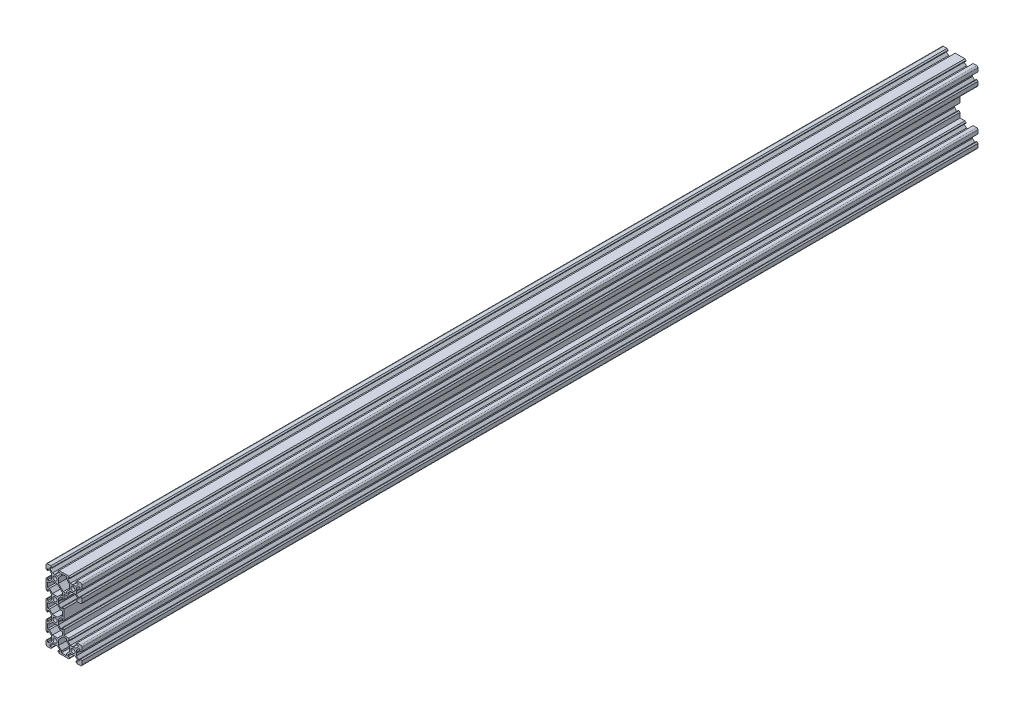
SolidWorks part; units mm, degrees
material "6061-T6 (SS)"
ref_plane "Front Plane" through (0, 0, 0) normal (0, 0, 1) x (1, 0, 0)
ref_plane "Top Plane" through (0, 0, 0) normal (0, 1, 0) x (1, 0, 0)
ref_plane "Right Plane" through (0, 0, 0) normal (1, 0, 0) x (0, 0, -1)
sketch "Sketch1" plane through (0, 0, 0) normal (0, 0, 1) x (1, 0, 0)
  line L0 (-20, -38.5) -> (-20, 38.5)
  line L1 (-18.5, 40) -> (18.5, 40)
  line L2 (20, 38.5) -> (20, 21.5)
  line L3 (18.5, 20) -> (0, 20)
  line L4 (0, 20) -> (0, -20)
  line L5 (0, 0) -> (-20, 0) construction
  line L6 (18.5, -20) -> (0, -20)
  line L7 (20, -38.5) -> (20, -21.5)
  line L8 (-18.5, -40) -> (18.5, -40)
  line L9 (20, 30) -> (10, 30) construction
  line L10 (-10, 0) -> (-10, 10) construction
  arc A0 (-18.5, -40) -> (-20, -38.5) centre (-18.5, -38.5) cw
  arc A1 (20, -38.5) -> (18.5, -40) centre (18.5, -38.5) cw
  arc A2 (18.5, -20) -> (20, -21.5) centre (18.5, -21.5) cw
  arc A3 (20, 21.5) -> (18.5, 20) centre (18.5, 21.5) cw
  arc A4 (18.5, 40) -> (20, 38.5) centre (18.5, 38.5) cw
  arc A5 (-20, 38.5) -> (-18.5, 40) centre (-18.5, 38.5) cw
  circle A6 centre (10, 30) radius 2.3
  circle A7 centre (-10, 30) radius 2.3
  circle A8 centre (-10, 10) radius 2.3
  circle A9 centre (-10, -10) radius 2.3
  circle A10 centre (10, -30) radius 2.3
  circle A11 centre (-10, -30) radius 2.3
  point P13 (-20, -40)
  point P16 (20, -40)
  point P19 (20, -20)
  point P22 (20, 20)
  point P25 (20, 40)
  point P28 (-20, 40)
  line B0 (-10, 30) -> (-10, 40) construction
  line B1 (-10, 33.69) -> (-10.21, 33.9)
  line B2 (-10.21, 33.9) -> (-12.8393, 33.9)
  line B3 (-12.8393, 33.9) -> (-15.5, 36.5607)
  line B4 (-15.5, 36.5607) -> (-15.5, 38.2)
  line B5 (-15.5, 38.2) -> (-13.395, 38.2)
  line B6 (-13.395, 38.2) -> (-13.395, 38.815)
  line B7 (-13.395, 38.815) -> (-14.58, 40)
  line B8 (-14.58, 40) -> (-5.42, 40)
  line B9 (-10, 30) -> (-15.9132, 35.9132) construction
  line B10 (-6.605, 38.815) -> (-5.42, 40)
  line B11 (-6.605, 38.2) -> (-6.605, 38.815)
  line B12 (-4.5, 38.2) -> (-6.605, 38.2)
  line B13 (-4.5, 36.5607) -> (-4.5, 38.2)
  line B14 (-7.1607, 33.9) -> (-4.5, 36.5607)
  line B15 (-9.79, 33.9) -> (-7.1607, 33.9)
  line B16 (-10, 33.69) -> (-9.79, 33.9)
  line B17 (10, 30) -> (10, 40) construction
  line B18 (10, 33.69) -> (9.79, 33.9)
  line B19 (9.79, 33.9) -> (7.1607, 33.9)
  line B20 (7.1607, 33.9) -> (4.5, 36.5607)
  line B21 (4.5, 36.5607) -> (4.5, 38.2)
  line B22 (4.5, 38.2) -> (6.605, 38.2)
  line B23 (6.605, 38.2) -> (6.605, 38.815)
  line B24 (6.605, 38.815) -> (5.42, 40)
  line B25 (5.42, 40) -> (14.58, 40)
  line B26 (10, 30) -> (4.0868, 35.9132) construction
  line B27 (13.395, 38.815) -> (14.58, 40)
  line B28 (13.395, 38.2) -> (13.395, 38.815)
  line B29 (15.5, 38.2) -> (13.395, 38.2)
  line B30 (15.5, 36.5607) -> (15.5, 38.2)
  line B31 (12.8393, 33.9) -> (15.5, 36.5607)
  line B32 (10.21, 33.9) -> (12.8393, 33.9)
  line B33 (10, 33.69) -> (10.21, 33.9)
  line B34 (10, -30) -> (10, -20) construction
  line B35 (10, -26.31) -> (9.79, -26.1)
  line B36 (9.79, -26.1) -> (7.1607, -26.1)
  line B37 (7.1607, -26.1) -> (4.5, -23.4393)
  line B38 (4.5, -23.4393) -> (4.5, -21.8)
  line B39 (4.5, -21.8) -> (6.605, -21.8)
  line B40 (6.605, -21.8) -> (6.605, -21.185)
  line B41 (6.605, -21.185) -> (5.42, -20)
  line B42 (5.42, -20) -> (14.58, -20)
  line B43 (10, -30) -> (4.0868, -24.0868) construction
  line B44 (13.395, -21.185) -> (14.58, -20)
  line B45 (13.395, -21.8) -> (13.395, -21.185)
  line B46 (15.5, -21.8) -> (13.395, -21.8)
  line B47 (15.5, -23.4393) -> (15.5, -21.8)
  line B48 (12.8393, -26.1) -> (15.5, -23.4393)
  line B49 (10.21, -26.1) -> (12.8393, -26.1)
  line B50 (10, -26.31) -> (10.21, -26.1)
  line B51 (-10, 30) -> (-20, 30) construction
  line B52 (-13.69, 30) -> (-13.9, 29.79)
  line B53 (-13.9, 29.79) -> (-13.9, 27.1607)
  line B54 (-13.9, 27.1607) -> (-16.5607, 24.5)
  line B55 (-16.5607, 24.5) -> (-18.2, 24.5)
  line B56 (-18.2, 24.5) -> (-18.2, 26.605)
  line B57 (-18.2, 26.605) -> (-18.815, 26.605)
  line B58 (-18.815, 26.605) -> (-20, 25.42)
  line B59 (-20, 25.42) -> (-20, 34.58)
  line B60 (-10, 30) -> (-15.9132, 24.0868) construction
  line B61 (-18.815, 33.395) -> (-20, 34.58)
  line B62 (-18.2, 33.395) -> (-18.815, 33.395)
  line B63 (-18.2, 35.5) -> (-18.2, 33.395)
  line B64 (-16.5607, 35.5) -> (-18.2, 35.5)
  line B65 (-13.9, 32.8393) -> (-16.5607, 35.5)
  line B66 (-13.9, 30.21) -> (-13.9, 32.8393)
  line B67 (-13.69, 30) -> (-13.9, 30.21)
  line B68 (-10, 10) -> (-20, 10) construction
  line B69 (-13.69, 10) -> (-13.9, 9.79)
  line B70 (-13.9, 9.79) -> (-13.9, 7.1607)
  line B71 (-13.9, 7.1607) -> (-16.5607, 4.5)
  line B72 (-16.5607, 4.5) -> (-18.2, 4.5)
  line B73 (-18.2, 4.5) -> (-18.2, 6.605)
  line B74 (-18.2, 6.605) -> (-18.815, 6.605)
  line B75 (-18.815, 6.605) -> (-20, 5.42)
  line B76 (-20, 5.42) -> (-20, 14.58)
  line B77 (-10, 10) -> (-15.9132, 4.0868) construction
  line B78 (-18.815, 13.395) -> (-20, 14.58)
  line B79 (-18.2, 13.395) -> (-18.815, 13.395)
  line B80 (-18.2, 15.5) -> (-18.2, 13.395)
  line B81 (-16.5607, 15.5) -> (-18.2, 15.5)
  line B82 (-13.9, 12.8393) -> (-16.5607, 15.5)
  line B83 (-13.9, 10.21) -> (-13.9, 12.8393)
  line B84 (-13.69, 10) -> (-13.9, 10.21)
  line B85 (-10, -10) -> (-20, -10) construction
  line B86 (-13.69, -10) -> (-13.9, -10.21)
  line B87 (-13.9, -10.21) -> (-13.9, -12.8393)
  line B88 (-13.9, -12.8393) -> (-16.5607, -15.5)
  line B89 (-16.5607, -15.5) -> (-18.2, -15.5)
  line B90 (-18.2, -15.5) -> (-18.2, -13.395)
  line B91 (-18.2, -13.395) -> (-18.815, -13.395)
  line B92 (-18.815, -13.395) -> (-20, -14.58)
  line B93 (-20, -14.58) -> (-20, -5.42)
  line B94 (-10, -10) -> (-15.9132, -15.9132) construction
  line B95 (-18.815, -6.605) -> (-20, -5.42)
  line B96 (-18.2, -6.605) -> (-18.815, -6.605)
  line B97 (-18.2, -4.5) -> (-18.2, -6.605)
  line B98 (-16.5607, -4.5) -> (-18.2, -4.5)
  line B99 (-13.9, -7.1607) -> (-16.5607, -4.5)
  line B100 (-13.9, -9.79) -> (-13.9, -7.1607)
  line B101 (-13.69, -10) -> (-13.9, -9.79)
  line B102 (-10, -30) -> (-20, -30) construction
  line B103 (-13.69, -30) -> (-13.9, -30.21)
  line B104 (-13.9, -30.21) -> (-13.9, -32.8393)
  line B105 (-13.9, -32.8393) -> (-16.5607, -35.5)
  line B106 (-16.5607, -35.5) -> (-18.2, -35.5)
  line B107 (-18.2, -35.5) -> (-18.2, -33.395)
  line B108 (-18.2, -33.395) -> (-18.815, -33.395)
  line B109 (-18.815, -33.395) -> (-20, -34.58)
  line B110 (-20, -34.58) -> (-20, -25.42)
  line B111 (-10, -30) -> (-15.9132, -35.9132) construction
  line B112 (-18.815, -26.605) -> (-20, -25.42)
  line B113 (-18.2, -26.605) -> (-18.815, -26.605)
  line B114 (-18.2, -24.5) -> (-18.2, -26.605)
  line B115 (-16.5607, -24.5) -> (-18.2, -24.5)
  line B116 (-13.9, -27.1607) -> (-16.5607, -24.5)
  line B117 (-13.9, -29.79) -> (-13.9, -27.1607)
  line B118 (-13.69, -30) -> (-13.9, -29.79)
  line B119 (-10, -30) -> (-10, -40) construction
  line B120 (-10, -33.69) -> (-9.79, -33.9)
  line B121 (-9.79, -33.9) -> (-7.1607, -33.9)
  line B122 (-7.1607, -33.9) -> (-4.5, -36.5607)
  line B123 (-4.5, -36.5607) -> (-4.5, -38.2)
  line B124 (-4.5, -38.2) -> (-6.605, -38.2)
  line B125 (-6.605, -38.2) -> (-6.605, -38.815)
  line B126 (-6.605, -38.815) -> (-5.42, -40)
  line B127 (-5.42, -40) -> (-14.58, -40)
  line B128 (-10, -30) -> (-4.0868, -35.9132) construction
  line B129 (-13.395, -38.815) -> (-14.58, -40)
  line B130 (-13.395, -38.2) -> (-13.395, -38.815)
  line B131 (-15.5, -38.2) -> (-13.395, -38.2)
  line B132 (-15.5, -36.5607) -> (-15.5, -38.2)
  line B133 (-12.8393, -33.9) -> (-15.5, -36.5607)
  line B134 (-10.21, -33.9) -> (-12.8393, -33.9)
  line B135 (-10, -33.69) -> (-10.21, -33.9)
  line B136 (10, -30) -> (10, -40) construction
  line B137 (10, -33.69) -> (10.21, -33.9)
  line B138 (10.21, -33.9) -> (12.8393, -33.9)
  line B139 (12.8393, -33.9) -> (15.5, -36.5607)
  line B140 (15.5, -36.5607) -> (15.5, -38.2)
  line B141 (15.5, -38.2) -> (13.395, -38.2)
  line B142 (13.395, -38.2) -> (13.395, -38.815)
  line B143 (13.395, -38.815) -> (14.58, -40)
  line B144 (14.58, -40) -> (5.42, -40)
  line B145 (10, -30) -> (15.9132, -35.9132) construction
  line B146 (6.605, -38.815) -> (5.42, -40)
  line B147 (6.605, -38.2) -> (6.605, -38.815)
  line B148 (4.5, -38.2) -> (6.605, -38.2)
  line B149 (4.5, -36.5607) -> (4.5, -38.2)
  line B150 (7.1607, -33.9) -> (4.5, -36.5607)
  line B151 (9.79, -33.9) -> (7.1607, -33.9)
  line B152 (10, -33.69) -> (9.79, -33.9)
  line B153 (10, 30) -> (10, 20) construction
  line B154 (10, 26.31) -> (10.21, 26.1)
  line B155 (10.21, 26.1) -> (12.8393, 26.1)
  line B156 (12.8393, 26.1) -> (15.5, 23.4393)
  line B157 (15.5, 23.4393) -> (15.5, 21.8)
  line B158 (15.5, 21.8) -> (13.395, 21.8)
  line B159 (13.395, 21.8) -> (13.395, 21.185)
  line B160 (13.395, 21.185) -> (14.58, 20)
  line B161 (14.58, 20) -> (5.42, 20)
  line B162 (10, 30) -> (15.9132, 24.0868) construction
  line B163 (6.605, 21.185) -> (5.42, 20)
  line B164 (6.605, 21.8) -> (6.605, 21.185)
  line B165 (4.5, 21.8) -> (6.605, 21.8)
  line B166 (4.5, 23.4393) -> (4.5, 21.8)
  line B167 (7.1607, 26.1) -> (4.5, 23.4393)
  line B168 (9.79, 26.1) -> (7.1607, 26.1)
  line B169 (10, 26.31) -> (9.79, 26.1)
  line B170 (-10, 10) -> (0, 10) construction
  line B171 (-6.31, 10) -> (-6.1, 10.21)
  line B172 (-6.1, 10.21) -> (-6.1, 12.8393)
  line B173 (-6.1, 12.8393) -> (-3.4393, 15.5)
  line B174 (-3.4393, 15.5) -> (-1.8, 15.5)
  line B175 (-1.8, 15.5) -> (-1.8, 13.395)
  line B176 (-1.8, 13.395) -> (-1.185, 13.395)
  line B177 (-1.185, 13.395) -> (0, 14.58)
  line B178 (0, 14.58) -> (0, 5.42)
  line B179 (-10, 10) -> (-4.0868, 15.9132) construction
  line B180 (-1.185, 6.605) -> (0, 5.42)
  line B181 (-1.8, 6.605) -> (-1.185, 6.605)
  line B182 (-1.8, 4.5) -> (-1.8, 6.605)
  line B183 (-3.4393, 4.5) -> (-1.8, 4.5)
  line B184 (-6.1, 7.1607) -> (-3.4393, 4.5)
  line B185 (-6.1, 9.79) -> (-6.1, 7.1607)
  line B186 (-6.31, 10) -> (-6.1, 9.79)
  line B187 (-10, -10) -> (0, -10) construction
  line B188 (-6.31, -10) -> (-6.1, -9.79)
  line B189 (-6.1, -9.79) -> (-6.1, -7.1607)
  line B190 (-6.1, -7.1607) -> (-3.4393, -4.5)
  line B191 (-3.4393, -4.5) -> (-1.8, -4.5)
  line B192 (-1.8, -4.5) -> (-1.8, -6.605)
  line B193 (-1.8, -6.605) -> (-1.185, -6.605)
  line B194 (-1.185, -6.605) -> (0, -5.42)
  line B195 (0, -5.42) -> (0, -14.58)
  line B196 (-10, -10) -> (-4.0868, -4.0868) construction
  line B197 (-1.185, -13.395) -> (0, -14.58)
  line B198 (-1.8, -13.395) -> (-1.185, -13.395)
  line B199 (-1.8, -15.5) -> (-1.8, -13.395)
  line B200 (-3.4393, -15.5) -> (-1.8, -15.5)
  line B201 (-6.1, -12.8393) -> (-3.4393, -15.5)
  line B202 (-6.1, -10.21) -> (-6.1, -12.8393)
  line B203 (-6.31, -10) -> (-6.1, -10.21)
  line B204 (10, -30) -> (20, -30) construction
  line B205 (13.69, -30) -> (13.9, -29.79)
  line B206 (13.9, -29.79) -> (13.9, -27.1607)
  line B207 (13.9, -27.1607) -> (16.5607, -24.5)
  line B208 (16.5607, -24.5) -> (18.2, -24.5)
  line B209 (18.2, -24.5) -> (18.2, -26.605)
  line B210 (18.2, -26.605) -> (18.815, -26.605)
  line B211 (18.815, -26.605) -> (20, -25.42)
  line B212 (20, -25.42) -> (20, -34.58)
  line B213 (10, -30) -> (15.9132, -24.0868) construction
  line B214 (18.815, -33.395) -> (20, -34.58)
  line B215 (18.2, -33.395) -> (18.815, -33.395)
  line B216 (18.2, -35.5) -> (18.2, -33.395)
  line B217 (16.5607, -35.5) -> (18.2, -35.5)
  line B218 (13.9, -32.8393) -> (16.5607, -35.5)
  line B219 (13.9, -30.21) -> (13.9, -32.8393)
  line B220 (13.69, -30) -> (13.9, -30.21)
  line B221 (10, 30) -> (20, 30) construction
  line B222 (13.69, 30) -> (13.9, 30.21)
  line B223 (13.9, 30.21) -> (13.9, 32.8393)
  line B224 (13.9, 32.8393) -> (16.5607, 35.5)
  line B225 (16.5607, 35.5) -> (18.2, 35.5)
  line B226 (18.2, 35.5) -> (18.2, 33.395)
  line B227 (18.2, 33.395) -> (18.815, 33.395)
  line B228 (18.815, 33.395) -> (20, 34.58)
  line B229 (20, 34.58) -> (20, 25.42)
  line B230 (10, 30) -> (15.9132, 35.9132) construction
  line B231 (18.815, 26.605) -> (20, 25.42)
  line B232 (18.2, 26.605) -> (18.815, 26.605)
  line B233 (18.2, 24.5) -> (18.2, 26.605)
  line B234 (16.5607, 24.5) -> (18.2, 24.5)
  line B235 (13.9, 27.1607) -> (16.5607, 24.5)
  line B236 (13.9, 29.79) -> (13.9, 27.1607)
  line B237 (13.69, 30) -> (13.9, 29.79)
  line B238 (-18.2, -2.7) -> (-18.2, 2.7)
  line B239 (-18.2, 2.7) -> (-16.2393, 2.7)
  line B240 (-16.2393, 2.7) -> (-12.8393, 6.1)
  line B241 (-12.8393, 6.1) -> (-7.1607, 6.1)
  line B242 (-10, 6.1) -> (-10, 0) construction
  line B243 (-10, 0) -> (-18.2, 0) construction
  line B244 (-3.7607, 2.7) -> (-7.1607, 6.1)
  line B245 (-1.8, 2.7) -> (-3.7607, 2.7)
  line B246 (-1.8, -2.7) -> (-1.8, 2.7)
  line B247 (-1.8, -2.7) -> (-3.7607, -2.7)
  line B248 (-3.7607, -2.7) -> (-7.1607, -6.1)
  line B249 (-12.8393, -6.1) -> (-7.1607, -6.1)
  line B250 (-16.2393, -2.7) -> (-12.8393, -6.1)
  line B251 (-18.2, -2.7) -> (-16.2393, -2.7)
  line B252 (-10, 6.1) -> (-10, 10) construction
  line B253 (-10, 10) -> (-15.0927, 4.9073) construction
  line B254 (-18.2, 17.3) -> (-18.2, 22.7)
  line B255 (-18.2, 22.7) -> (-16.2393, 22.7)
  line B256 (-16.2393, 22.7) -> (-12.8393, 26.1)
  line B257 (-12.8393, 26.1) -> (-7.1607, 26.1)
  line B258 (-10, 26.1) -> (-10, 20) construction
  line B259 (-10, 20) -> (-18.2, 20) construction
  line B260 (-1.8, 17.3) -> (-3.7607, 17.3)
  line B261 (-3.7607, 17.3) -> (-7.1607, 13.9)
  line B262 (-12.8393, 13.9) -> (-7.1607, 13.9)
  line B263 (-16.2393, 17.3) -> (-12.8393, 13.9)
  line B264 (-18.2, 17.3) -> (-16.2393, 17.3)
  line B265 (-10, 26.1) -> (-10, 30) construction
  line B266 (-10, 30) -> (-15.0927, 24.9073) construction
  line B267 (-7.1607, 26.1) -> (-1.8, 20.7393)
  line B268 (-1.8, 17.3) -> (-1.8, 20.7393)
  line B269 (2.7, -38.2) -> (-2.7, -38.2)
  line B270 (-2.7, -38.2) -> (-2.7, -36.2393)
  line B271 (-2.7, -36.2393) -> (-6.1, -32.8393)
  line B272 (-6.1, -32.8393) -> (-6.1, -27.1607)
  line B273 (-6.1, -30) -> (0, -30) construction
  line B274 (0, -30) -> (0, -38.2) construction
  line B275 (2.7, -21.8) -> (2.7, -23.7607)
  line B276 (2.7, -23.7607) -> (6.1, -27.1607)
  line B277 (6.1, -32.8393) -> (6.1, -27.1607)
  line B278 (2.7, -36.2393) -> (6.1, -32.8393)
  line B279 (2.7, -38.2) -> (2.7, -36.2393)
  line B280 (-6.1, -30) -> (-10, -30) construction
  line B281 (-10, -30) -> (-4.9073, -35.0927) construction
  line B282 (-6.1, -27.1607) -> (-0.7393, -21.8)
  line B283 (2.7, -21.8) -> (-0.7393, -21.8)
  line B284 (-18.2, -22.7) -> (-18.2, -17.3)
  line B285 (-18.2, -17.3) -> (-16.2393, -17.3)
  line B286 (-16.2393, -17.3) -> (-12.8393, -13.9)
  line B287 (-12.8393, -13.9) -> (-7.1607, -13.9)
  line B288 (-10, -13.9) -> (-10, -20) construction
  line B289 (-10, -20) -> (-18.2, -20) construction
  line B290 (-12.8393, -26.1) -> (-7.1607, -26.1)
  line B291 (-16.2393, -22.7) -> (-12.8393, -26.1)
  line B292 (-18.2, -22.7) -> (-16.2393, -22.7)
  line B293 (-10, -13.9) -> (-10, -10) construction
  line B294 (-10, -10) -> (-15.0927, -15.0927) construction
  line B295 (-3.7607, -17.3) -> (-7.1607, -13.9)
  line B296 (-1.8, -17.3) -> (-3.7607, -17.3)
  line B297 (-1.8, -17.3) -> (-1.8, -20.7393)
  line B298 (-1.8, -20.7393) -> (-7.1607, -26.1)
  line B299 (-2.7, 38.2) -> (2.7, 38.2)
  line B300 (2.7, 38.2) -> (2.7, 36.2393)
  line B301 (2.7, 36.2393) -> (6.1, 32.8393)
  line B302 (6.1, 32.8393) -> (6.1, 27.1607)
  line B303 (6.1, 30) -> (0, 30) construction
  line B304 (0, 30) -> (0, 38.2) construction
  line B305 (-6.1, 32.8393) -> (-6.1, 27.1607)
  line B306 (-2.7, 36.2393) -> (-6.1, 32.8393)
  line B307 (-2.7, 38.2) -> (-2.7, 36.2393)
  line B308 (6.1, 30) -> (10, 30) construction
  line B309 (10, 30) -> (4.9073, 35.0927) construction
  line B310 (2.7, 23.7607) -> (6.1, 27.1607)
  line B311 (2.7, 21.8) -> (2.7, 23.7607)
  line B312 (2.7, 21.8) -> (-0.7393, 21.8)
  line B313 (-0.7393, 21.8) -> (-6.1, 27.1607)
  dimension "D3" = 1.5
  dimension "D6" = 4.6
  dimension "D7" = 20
  dimension "D8" = 20
  dimension "D1" = 40
  dimension "D2" = 80
  dimension "D4" = 20
  dimension "D5" = 20
sketch_block_instance "V Slot 2-1"
sketch_block "V Slot 2" parameters "D1"=10, "D2"=11, "D3"=4.3, "D4"=1.8, "D5"=0.21, "D6"=45, "D7"=9.16, "D8"=1.5, "D9"=6.79
sketch_block_instance "V Slot 2-2"
sketch_block_instance "V Slot 2-3"
sketch_block_instance "V Slot 2-4"
sketch_block_instance "V Slot 2-5"
sketch_block_instance "V Slot 2-6"
sketch_block_instance "V Slot 2-7"
sketch_block_instance "V Slot 2-8"
sketch_block_instance "V Slot 2-9"
sketch_block_instance "V Slot 2-10"
sketch_block_instance "V Slot 2-11"
sketch_block_instance "V Slot 2-12"
sketch_block_instance "V Slot 2-13"
sketch_block_instance "V Slot 2-14"
sketch_block_instance "Center Cutout 1-1"
sketch_block "Center Cutout 1" parameters "D1"=5.4, "D2"=12.2, "D3"=8.2, "D4"=45, "D5"=10, "D6"=1.5
sketch_block_instance "Corner Cutout 1-1"
sketch_block "Corner Cutout 1" parameters "D1"=5.4, "D2"=12.2, "D3"=8.2, "D4"=45, "D5"=10, "D6"=1.5
sketch_block_instance "Corner Cutout 1-2"
sketch_block_instance "Corner Cutout 2-1"
sketch_block "Corner Cutout 2" parameters "D1"=5.4, "D2"=12.2, "D3"=8.2, "D4"=45, "D5"=10, "D6"=1.5
sketch_block_instance "Corner Cutout 2-2"
extrude "Boss-Extrude1" add sketch "Sketch1" along normal blind 1000 contours B237 B222 B223 B224 B225 B226 B227 B228 L2 A4 L1 B27 B28 B29 B30 B31 B32 B33 B18 B19 B20 B21 B22 B23 B24 B10 B11 B12 B13 B14 B15 B16 B1 B2 B3 B4 B5 B6 B7 A5 L0 B61 B62 B63 B64 B65 B66 B67 B52
ref_plane "Plane1" through (10, 0, 0) normal (-1, 0, 0) x (0, 0, 1)
